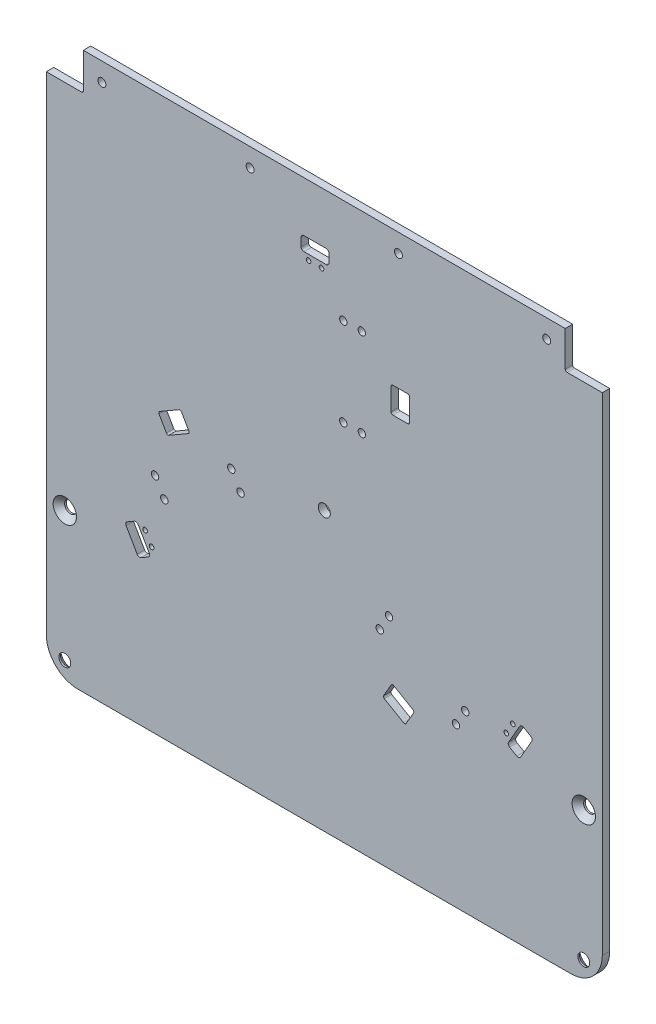
SolidWorks part; units mm, degrees
ref_plane "Ebene vorne" through (0, 0, 0) normal (0, 0, 1) x (1, 0, 0)
ref_plane "Ebene oben" through (0, 0, 0) normal (0, 1, 0) x (1, 0, 0)
ref_plane "Ebene rechts" through (0, 0, 0) normal (1, 0, 0) x (0, 0, -1)
sketch "Skizze1" plane through (0, 0, 0) normal (0, 0, 1) x (1, 0, 0)
  line L0 (0, 150) -> (300, 150) construction
  line L1 (0, 0) -> (300, 0)
  line L2 (0, 0) -> (0, 300)
  line L3 (0, 300) -> (300, 300)
  line L4 (300, 0) -> (300, 300)
  line L5 (150, 300) -> (150, 0) construction
  circle A0 centre (150, 150) radius 3.25
  dimension "D2" = 6.5
  dimension "D1" = 300
extrude "Aufsatz-Linear austragen1" add sketch "Skizze1" along normal blind 4
sketch "Skizze2" plane through (0, 0, 4) normal (0, 0, 1) x (1, 0, 0)
  line L0 (150, 150) -> (150, 220) construction
  line L1 (150, 150) -> (89.3782, 115) construction
  line L2 (150, 150) -> (210.6218, 115) construction
  line L3 (300, 300) -> (0, 300) construction
  dimension "D1" = 70
  dimension "D2" = 120
  dimension "D3" = 120
hole_wizard "Ø4.0 (4) Durchmesser Bohrung1" positions "Skizze4" profile "Skizze3" hole size "Ø4.0" standard "DIN" end condition up to next
sketch "Skizze4" plane through (0, 0, 4) normal (0, 0, 1) x (1, 0, 0)
  line L1 (160.25, 196.25) -> (170.25, 196.25) construction
  line L2 (160.25, 196.25) -> (160.25, 243.75) construction
  line L3 (160.25, 243.75) -> (170.25, 243.75) construction
  line L4 (170.25, 196.25) -> (170.25, 243.75) construction
  circle A0 centre (150, 150) radius 3.25 construction
  point P1 (160.25, 196.25)
  point P2 (170.25, 243.75)
  point P5 (160.25, 243.75)
  point P6 (170.25, 196.25)
  dimension "D3" = 46.25
  dimension "D1" = 10
  dimension "D2" = 47.5
  dimension "D4" = 10.25
sketch "Skizze3" plane through (160.25, 196.25, 4) normal (1, 0, 0) x (0, -1, 0)
  line L0 (0, 0) -> (0, 4.001)
  line L1 (0, 4.001) -> (2, 4.001)
  line L2 (2, 4.001) -> (2, 0)
  line L5 (2, 0) -> (0, 0)
  line L11 (0, -6.35) -> (0, 107.95) construction
  dimension "Bohrerdurchmesser" = 4
  dimension "Bohrungstiefe" = 4.001
hole_wizard "M3 Gewindebohrung1" positions "Skizze6" profile "Skizze5" tap size "M3" standard "DIN"
sketch "Skizze6" plane through (0, 0, 4) normal (0, 0, 1) x (1, 0, 0)
  circle A0 centre (150, 150) radius 3.25 construction
  point P0 (148.5, 262.5)
  point P2 (141.5, 262.5)
  dimension "D1" = 112.5
  dimension "D2" = 1.5
  dimension "D3" = 7
sketch "Skizze5" plane through (148.5, 262.5, 4) normal (1, 0, 0) x (0, -1, 0)
  line L0 (0, 0) -> (0, 9.2511)
  line L1 (0, 9.2511) -> (1.25, 8.5)
  line L2 (1.25, 8.5) -> (1.25, 0)
  line L5 (1.25, 0) -> (0, 0)
  line L10 (0, 9.2511) -> (-1.25, 8.5) construction
  line L11 (0, -6.35) -> (0, 107.95) construction
  dimension "Bohrerdurchmesser" = 2.5
  dimension "Bohrungstiefe" = 8.5
  dimension "Spitzenwinkel" = 118
cosmetic thread "Bohrungsgewinde5" parameters "D1"=4, "D2"=3
cosmetic thread "Bohrungsgewinde6" parameters "D1"=4, "D2"=3
sketch "Skizze8" plane through (0, 0, 0) normal (0, 0, -1) x (-1, 0, 0)
  circle A0 centre (-213, 220) radius 9.5
  circle A1 centre (-150, 150) radius 3.25 construction
  dimension "D1" = 63
  dimension "D2" = 70
  dimension "D3" = 19
extrude "Schnitt-Linear austragen1" [suppressed] cut sketch "Skizze8" against normal up to next
sketch "Skizze9" plane through (0, 0, 4) normal (0, 0, 1) x (1, 0, 0)
  line L1 (139, 272.9) -> (151, 272.9)
  line L2 (137.5, 271.4) -> (137.5, 266.9)
  line L3 (139, 265.4) -> (151, 265.4)
  line L4 (152.5, 271.4) -> (152.5, 266.9)
  arc A0 (151, 272.9) -> (152.5, 271.4) centre (151, 271.4) cw
  arc A1 (151, 265.4) -> (152.5, 266.9) centre (151, 266.9) ccw
  arc A2 (137.5, 266.9) -> (139, 265.4) centre (139, 266.9) ccw
  arc A3 (139, 272.9) -> (137.5, 271.4) centre (139, 271.4) ccw
  circle A4 centre (150, 150) radius 3.25 construction
  point P8 (152.5, 265.4)
  point P11 (137.5, 265.4)
  point P14 (137.5, 272.9)
  dimension "D3" = 1.5
  dimension "D1" = 7.5
  dimension "D2" = 15
  dimension "D4" = 2.5
  dimension "D5" = 115.4
extrude "Schnitt-Linear austragen2" cut sketch "Skizze9" against normal up to next
sketch "Skizze16" plane through (0, 0, 4) normal (0, 0, 1) x (1, 0, 0)
  line L1 (195, 227) -> (187, 227)
  line L2 (196, 226) -> (196, 214)
  line L3 (195, 213) -> (187, 213)
  line L4 (186, 226) -> (186, 214)
  circle A1 centre (150, 150) radius 3.25 construction
  arc A2 (196, 214) -> (195, 213) centre (195, 214) cw
  arc A3 (187, 213) -> (186, 214) centre (187, 214) cw
  arc A4 (187, 227) -> (186, 226) centre (187, 226) ccw
  arc A5 (195, 227) -> (196, 226) centre (195, 226) cw
  point P8 (196, 213)
  point P13 (186, 227)
  point P16 (196, 227)
  dimension "D1" = 63
  dimension "D5" = 1
  dimension "D2" = 14
  dimension "D3" = 10
  dimension "D4" = 36
extrude "Schnitt-Linear austragen4" cut sketch "Skizze16" against normal up to next
pattern_circular "Kreismuster1" count 3 over 360 about axis through (150, 150, 0) along (0, 0, 1) of "Ø4.0 (4) Durchmesser Bohrung1", "M3 Gewindebohrung1", "Schnitt-Linear austragen1", "Schnitt-Linear austragen2", "Schnitt-Linear austragen4"
sketch "Skizze12" plane through (0, 0, 0) normal (0, 0, -1) x (-1, 0, 0)
  line L0 (-300, 17) -> (-300, 0)
  line L1 (-300, 300) -> (-280, 300)
  line L2 (-300, 300) -> (-300, 280)
  line L3 (-300, 280) -> (-281, 280)
  line L4 (-280, 300) -> (-280, 281)
  line L5 (0, 300) -> (-20, 300)
  line L6 (0, 300) -> (0, 280)
  line L7 (0, 280) -> (-19, 280)
  line L8 (-20, 300) -> (-20, 281)
  line L9 (-300, 0) -> (-283, 0)
  line L10 (-17, 0) -> (0, 0)
  line L11 (0, 0) -> (-300, 0) construction
  line L12 (0, 0) -> (0, 17)
  line L13 (0, 300) -> (0, 0) construction
  arc A0 (0, 17) -> (-17, 0) centre (-17, 17) cw
  arc A1 (-300, 17) -> (-283, 0) centre (-283, 17) ccw
  arc A2 (-19, 280) -> (-20, 281) centre (-19, 281) cw
  arc A3 (-281, 280) -> (-280, 281) centre (-281, 281) ccw
  point P28 (-280, 280)
  point P34 (-300, 0)
  dimension "D4" = 17
  dimension "D1" = 20
extrude "Schnitt-Linear austragen3" cut sketch "Skizze12" against normal up to next
hole_wizard "Formsenkung für M6 Senkschraube mit Schlitz/Kreuzschlitz1" positions "Skizze15" profile "Skizze14" countersink size "M6" standard "DIN" end condition through all
sketch "Skizze15" plane through (0, 0, 0) normal (0, 0, -1) x (-1, 0, 0)
  line L0 (-300, 17) -> (-300, 280) construction
  line L1 (-17, 0) -> (-283, 0) construction
  line L2 (0, 280) -> (0, 17) construction
  point P0 (-290, 10)
  point P2 (-10, 10)
  dimension "D1" = 10
  dimension "D2" = 10
  dimension "D3" = 10
  dimension "D4" = 10
sketch "Skizze14" plane through (290, 10, 0) normal (1, 0, 0) x (0, 1, 0)
  line L0 (0, 0) -> (0, 4)
  line L1 (0, 4) -> (3.2, 4)
  line L2 (3.2, 4) -> (3.2, 3.1)
  line L3 (3.2, 3.1) -> (6.3, 0)
  line L5 (6.3, 0) -> (0, 0)
  line L6 (-3.2, 3.1) -> (-6.3, 0) construction
  line L11 (0, -6.35) -> (0, 107.95) construction
  dimension "Bohrerdurchmesser" = 6.4
  dimension "Bohrungstiefe" = 4
  dimension "Senkdurchmesser (Oben)" = 12.6
  dimension "Senkwinkel (Oben)" = 90
hole_wizard "Ø4.3 (4.3) Durchmesser Bohrung1" positions "Skizze18" profile "Skizze17" hole size "Ø4.3" standard "ISO"
sketch "Skizze18" plane through (0, 0, 4) normal (0, 0, 1) x (1, 0, 0)
  line L0 (30, 290) -> (110, 290) construction
  line L1 (110, 290) -> (190, 290) construction
  line L2 (190, 290) -> (270, 290) construction
  line L5 (30, 290) -> (20, 290) construction
  line L6 (20, 281) -> (20, 300) construction
  line L9 (270, 290) -> (280, 290) construction
  line L10 (280, 300) -> (280, 281) construction
  line L13 (280, 300) -> (20, 300) construction
  point P0 (30, 290)
  point P2 (110, 290)
  point P4 (190, 290)
  point P6 (270, 290)
  dimension "D1" = 240
  dimension "D2" = 10
sketch "Skizze17" plane through (30, 290, 4) normal (1, 0, 0) x (0, -1, 0)
  line L0 (0, 0) -> (0, 4)
  line L1 (0, 4) -> (2.15, 4)
  line L2 (2.15, 4) -> (2.15, 0)
  line L5 (2.15, 0) -> (0, 0)
  line L10 (0, 4) -> (-2.15, 4) construction
  line L11 (0, -6.35) -> (0, 107.95) construction
  dimension "Bohrerdurchmesser" = 4.3
  dimension "Bohrungstiefe" = 4
  dimension "Spitzenwinkel" = 180
hole_wizard "Formsenkung für M6 Senkschraube mit Schlitz/Kreuzschlitz2" positions "Skizze20" profile "Skizze19" countersink size "M6" standard "DIN" end condition through all
sketch "Skizze20" plane through (0, 0, 4) normal (0, 0, 1) x (1, 0, 0)
  line L0 (280, 300) -> (20, 300) construction
  line L1 (300, 17) -> (300, 280) construction
  line L2 (0, 280) -> (0, 17) construction
  point P0 (10, 80)
  point P2 (290, 80)
  dimension "D1" = 220
  dimension "D2" = 10
  dimension "D3" = 10
sketch "Skizze19" plane through (10, 80, 4) normal (1, 0, 0) x (0, -1, 0)
  line L0 (0, 0) -> (0, 4)
  line L1 (0, 4) -> (3.2, 4)
  line L2 (3.2, 4) -> (3.2, 3.1)
  line L3 (3.2, 3.1) -> (6.3, 0)
  line L5 (6.3, 0) -> (0, 0)
  line L6 (-3.2, 3.1) -> (-6.3, 0) construction
  line L11 (0, -6.35) -> (0, 107.95) construction
  dimension "Bohrerdurchmesser" = 6.4
  dimension "Bohrungstiefe" = 4
  dimension "Senkdurchmesser (Oben)" = 12.6
  dimension "Senkwinkel (Oben)" = 90
